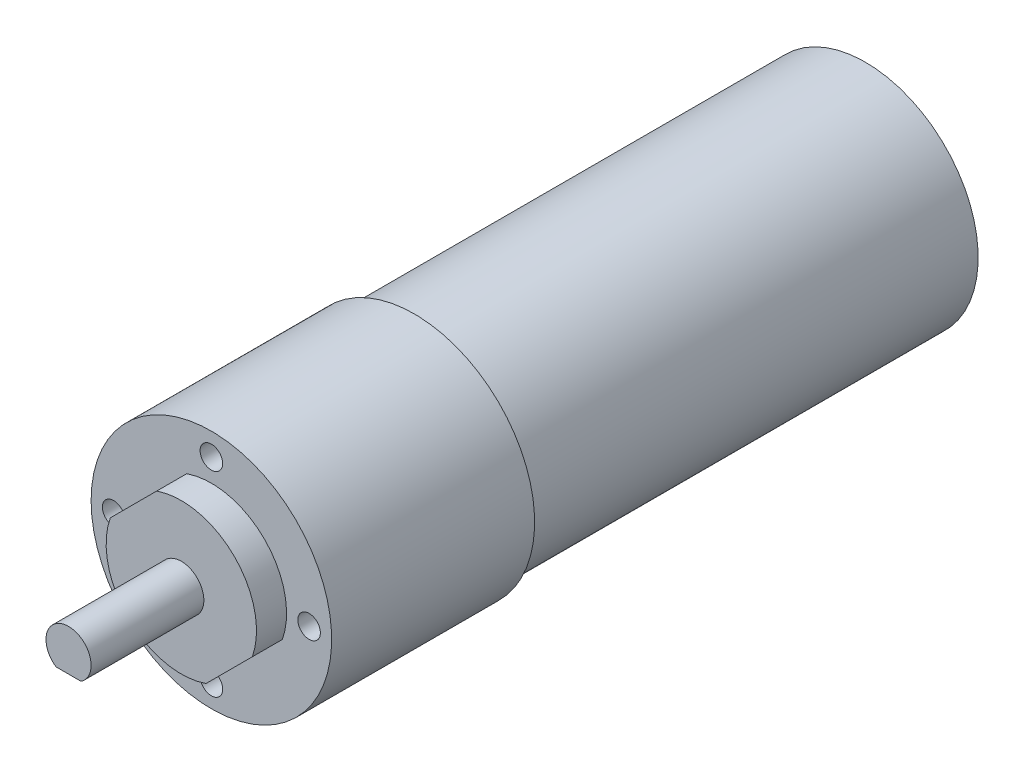
SolidWorks part; units mm, degrees
ref_plane "Front Plane" through (0, 0, 0) normal (0, 0, 1) x (1, 0, 0)
ref_plane "Top Plane" through (0, 0, 0) normal (0, 1, 0) x (1, 0, 0)
ref_plane "Right Plane" through (0, 0, 0) normal (1, 0, 0) x (0, 0, -1)
sketch "Sketch1" plane through (0, 0, 0) normal (0, 0, 1) x (1, 0, 0)
  circle A0 centre (0, 0) radius 3
  dimension "D1" = 6
extrude "Boss-Extrude1" add sketch "Sketch1" along normal blind 15
sketch "Sketch2" plane through (0, 0, 15) normal (0, 0, 1) x (1, 0, 0)
  line L1 (1.6583, -2.5) -> (-1.6583, -2.5)
  circle A1 centre (0, 0) radius 3
  arc A3 (-1.6583, -2.5) -> (1.6583, -2.5) centre (0, 0) ccw
  dimension "D2" = 2.5
  dimension "D1" = 0
extrude "Cut-Extrude2" cut sketch "Sketch2" against normal blind 12
sketch "Sketch3" plane through (0, 0, 0) normal (0, 0, -1) x (-1, 0, 0)
  circle A0 centre (0, 0) radius 10
  dimension "D1" = 20
extrude "Boss-Extrude2" add sketch "Sketch3" along normal blind 4
sketch "Sketch4" plane through (0, 0, -4) normal (0, 0, -1) x (-1, 0, 0)
  line L0 (-9.4462, 3.2818) -> (-3.2818, 9.4462) construction
  line L3 (9.4462, -3.2818) -> (3.2818, -9.4462) construction
  line L4 (-9.4462, 3.2818) -> (3.2818, -9.4462) construction
  line L5 (-3.2818, 9.4462) -> (9.4462, -3.2818) construction
  line L6 (0, 10) -> (0, 0) construction
  line L7 (0, 0) -> (-6.364, 6.364) construction
  line L8 (-9.4462, -3.2818) -> (-3.2818, -9.4462)
  line L9 (9.4462, 3.2818) -> (3.2818, 9.4462)
  arc A1 (3.2818, -9.4462) -> (9.4462, -3.2818) centre (0, 0) ccw construction
  circle A3 centre (0, 0) radius 10
  arc A4 (9.4462, 3.2818) -> (3.2818, 9.4462) centre (0, 0) ccw
  arc A5 (-3.2818, -9.4462) -> (-9.4462, -3.2818) centre (0, 0) cw
  arc A6 (-3.2818, 9.4462) -> (-9.4462, 3.2818) centre (0, 0) ccw construction
  circle M4 centre (0, 0) radius 10
  dimension "D2" = 18
  dimension "D3" = 45
  dimension "D1" = 0
extrude "Cut-Extrude3" cut sketch "Sketch4" against normal up to next contours L8 M4 | A4 L9
sketch "Sketch5" plane through (0, 0, -4) normal (0, 0, -1) x (-1, 0, 0)
  circle A0 centre (0, 0) radius 16
  dimension "D1" = 32
extrude "Boss-Extrude3" add sketch "Sketch5" along normal blind 27
sketch "Sketch6" plane through (0, 0, -31) normal (0, 0, -1) x (-1, 0, 0)
  circle A0 centre (0, 0) radius 15
  dimension "D1" = 30
extrude "Boss-Extrude4" add sketch "Sketch6" along normal blind 60
sketch "Sketch9" plane through (0, 0, -4) normal (0, 0, 1) x (1, 0, 0)
  circle A0 centre (0, 13) radius 1.5
  circle A1 centre (0, 0) radius 13 construction
  circle A2 centre (13, 0) radius 1.5
  circle A3 centre (0, -13) radius 1.5
  circle A4 centre (-13, 0) radius 1.5
  point P14 (0, 0)
  dimension "D1" = 3
  dimension "D2" = 26
  dimension "D3" = 4
extrude "Cut-Extrude4" cut sketch "Sketch9" against normal blind 5
